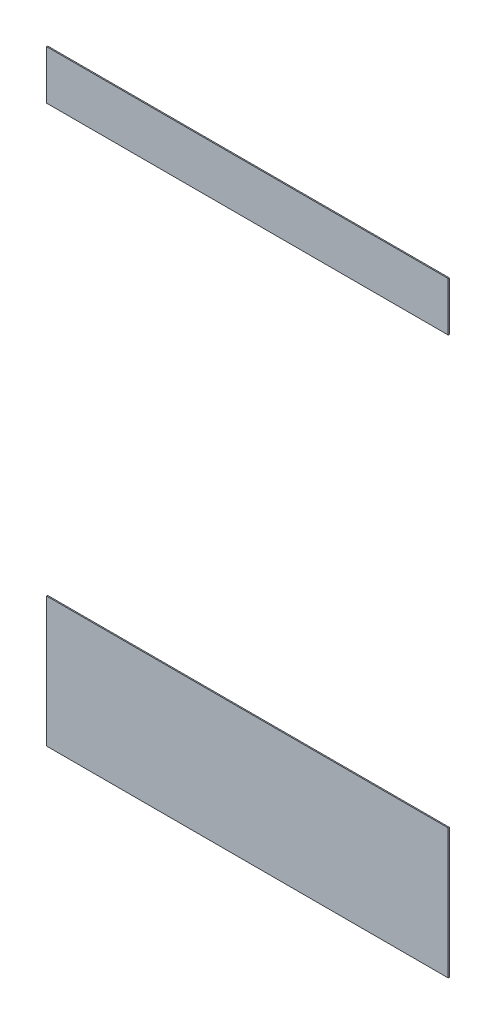
SolidWorks part; units mm, degrees
ref_plane "前视基准面" through (0, 0, 0) normal (0, 0, 1) x (1, 0, 0)
ref_plane "上视基准面" through (0, 0, 0) normal (0, 1, 0) x (1, 0, 0)
ref_plane "右视基准面" through (0, 0, 0) normal (1, 0, 0) x (0, 0, -1)
sketch "草图1" plane through (0, 0, 0) normal (0, 0, 1) x (1, 0, 0)
  line L1 (0, 126.5) -> (-360, 126.5)
  line L2 (0, 126.5) -> (0, 10)
  line L3 (0, 10) -> (-360, 10)
  line L4 (-360, 126.5) -> (-360, 10)
  line L5 (0, 553) -> (-360, 553)
  line L6 (0, 553) -> (0, 509.1055)
  line L7 (0, 509.1055) -> (-360, 509.1055)
  line L8 (-360, 553) -> (-360, 509.1055)
extrude "凸台-拉伸1" add sketch "草图1" against normal blind 1
sketch "草图2" plane through (0, 0, 0) normal (0, 0, 1) x (1, 0, 0)
  line L0 (31.3333, 111.3326) -> (156.6667, 111.3326) construction
  line L1 (24.5, 104.0776) -> (122.5, 104.0776) construction
